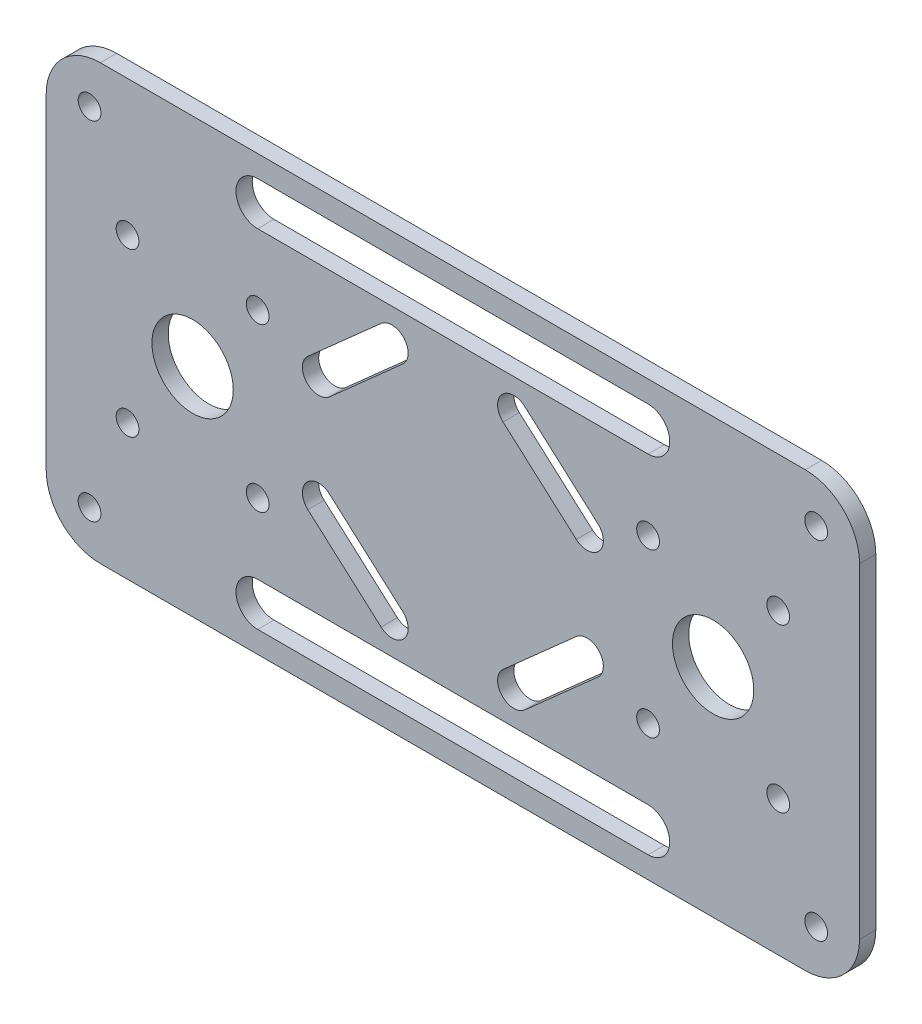
SolidWorks part; units mm, degrees
ref_plane "前视基准面" through (0, 0, 0) normal (0, 0, 1) x (1, 0, 0)
ref_plane "上视基准面" through (0, 0, 0) normal (0, 1, 0) x (1, 0, 0)
ref_plane "右视基准面" through (0, 0, 0) normal (1, 0, 0) x (0, 0, -1)
sketch "草图1" plane through (0, 0, 0) normal (0, 0, 1) x (1, 0, 0)
  line L0 (10, 0) -> (140, 0)
  line L1 (150, -10) -> (150, -70)
  line L2 (140, -80) -> (10, -80)
  line L3 (0, -70) -> (0, -10)
  arc A0 (140, 0) -> (150, -10) centre (140, -10) cw
  arc A1 (140, -80) -> (150, -70) centre (140, -70) ccw
  arc A2 (10, -80) -> (0, -70) centre (10, -70) cw
  arc A3 (10, 0) -> (0, -10) centre (10, -10) ccw
  circle A4 centre (8, -8) radius 2.1
  circle A5 centre (8, -72) radius 2.1
  circle A6 centre (142, -72) radius 2.1
  circle A7 centre (142, -8) radius 2.1
  point P7 (150, 0)
  point P10 (150, -80)
  point P15 (0, 0)
  point P24 (8.5108, -74.0192)
  point P26 (5.9364, -7.4879)
  dimension "D3" = 10
  dimension "D6" = 4.2
  dimension "D10" = 8
  dimension "D12" = 8
  dimension "D1" = 150
  dimension "D2" = 80
  dimension "D4" = 8
  dimension "D5" = 8
  dimension "D7" = 8
  dimension "D8" = 8
  dimension "D9" = 8
  dimension "D11" = 8
extrude "凸台-拉伸1" add sketch "草图1" along normal blind 3
sketch "草图2" plane through (0, 0, 3) normal (0, 0, 1) x (1, 0, 0)
  line L0 (0, -40) -> (150, -40) construction
  line L1 (0, -10) -> (0, -70) construction
  line L2 (150, -70) -> (150, -10) construction
  line L3 (75, 0) -> (75, -80) construction
  line L4 (140, 0) -> (10, 0) construction
  line L5 (10, -80) -> (140, -80) construction
  circle A0 centre (15, -25) radius 2.1
  circle A1 centre (39, -25) radius 2.1
  circle A2 centre (39, -55) radius 2.1
  circle A3 centre (15, -55) radius 2.1
  circle A4 centre (111, -55) radius 2.1
  circle A5 centre (111, -25) radius 2.1
  circle A6 centre (135, -25) radius 2.1
  circle A7 centre (135, -55) radius 2.1
  point P20 (0, 0)
  point P21 (19.7472, -32.6483)
  dimension "D2" = 24
  dimension "D3" = 30
  dimension "D4" = 4.2
  dimension "D1" = 15
extrude "切除-拉伸1" cut sketch "草图2" against normal blind 3
sketch "草图3" plane through (0, 0, 3) normal (0, 0, 1) x (1, 0, 0)
  line L0 (39, -25) -> (39, -8) construction
  line L1 (8, -8) -> (142, -8) construction
  line L2 (8, -8) -> (8, -72) construction
  line L3 (8, -72) -> (142, -72) construction
  line L4 (142, -8) -> (142, -72) construction
  line L5 (15, -25) -> (39, -25) construction
  line L6 (15, -25) -> (15, -55) construction
  line L7 (15, -55) -> (39, -55) construction
  line L8 (39, -25) -> (39, -55) construction
  line L9 (111, -25) -> (135, -25) construction
  line L10 (111, -25) -> (111, -55) construction
  line L11 (111, -55) -> (135, -55) construction
  line L12 (135, -25) -> (135, -55) construction
  line L13 (111, -25) -> (111, -8) construction
  line L14 (39, -8) -> (111, -8) construction
  line L15 (39, -4) -> (111, -4)
  line L16 (39, -12) -> (111, -12)
  line L17 (0, -40) -> (150, -40) construction
  line L18 (0, -10) -> (0, -70) construction
  line L19 (150, -70) -> (150, -10) construction
  line L20 (39, -72) -> (111, -72) construction
  line L21 (39, -76) -> (111, -76)
  line L22 (39, -68) -> (111, -68)
  line L23 (75, -8) -> (75, -72) construction
  line L24 (75, -8) -> (39, -40) construction
  line L25 (39, -40) -> (75, -72) construction
  line L26 (75, -72) -> (111, -40) construction
  line L27 (111, -40) -> (75, -8) construction
  line L28 (63.75, -18) -> (50.25, -30) construction
  line L29 (65.7431, -20.2422) -> (52.2431, -32.2422)
  line L30 (61.7569, -15.7578) -> (48.2569, -27.7578)
  line L31 (63.75, -62) -> (50.25, -50) construction
  line L32 (65.7431, -59.7578) -> (52.2431, -47.7578)
  line L33 (61.7569, -64.2422) -> (48.2569, -52.2422)
  line L34 (86.25, -18) -> (99.75, -30) construction
  line L35 (84.2569, -20.2422) -> (97.7569, -32.2422)
  line L36 (88.2431, -15.7578) -> (101.7431, -27.7578)
  line L37 (86.25, -62) -> (99.75, -50) construction
  line L38 (84.2569, -59.7578) -> (97.7569, -47.7578)
  line L39 (88.2431, -64.2422) -> (101.7431, -52.2422)
  arc A0 (39, -4) -> (39, -12) centre (39, -8) ccw
  arc A1 (111, -12) -> (111, -4) centre (111, -8) ccw
  arc A2 (39, -76) -> (39, -68) centre (39, -72) cw
  arc A3 (111, -68) -> (111, -76) centre (111, -72) cw
  circle A4 centre (27, -40) radius 7.5
  circle A5 centre (123, -40) radius 7.5
  arc A6 (65.7431, -20.2422) -> (61.7569, -15.7578) centre (63.75, -18) ccw
  arc A7 (48.2569, -27.7578) -> (52.2431, -32.2422) centre (50.25, -30) ccw
  arc A8 (65.7431, -59.7578) -> (61.7569, -64.2422) centre (63.75, -62) cw
  arc A9 (48.2569, -52.2422) -> (52.2431, -47.7578) centre (50.25, -50) cw
  arc A10 (84.2569, -20.2422) -> (88.2431, -15.7578) centre (86.25, -18) cw
  arc A11 (101.7431, -27.7578) -> (97.7569, -32.2422) centre (99.75, -30) cw
  arc A12 (84.2569, -59.7578) -> (88.2431, -64.2422) centre (86.25, -62) ccw
  arc A13 (101.7431, -52.2422) -> (97.7569, -47.7578) centre (99.75, -50) ccw
  point P18 (75, -8)
  point P33 (75, -72)
  point P48 (57, -24)
  point P55 (71.9616, -26.6405)
  point P56 (57, -56)
  point P63 (93, -24)
  point P70 (93, -56)
  dimension "D2" = 15
  dimension "D1" = 8
  dimension "D3" = 48
  dimension "D4" = 16
  dimension "D5" = 10
  dimension "D6" = 6
extrude "切除-拉伸2" cut sketch "草图3" against normal blind 3
